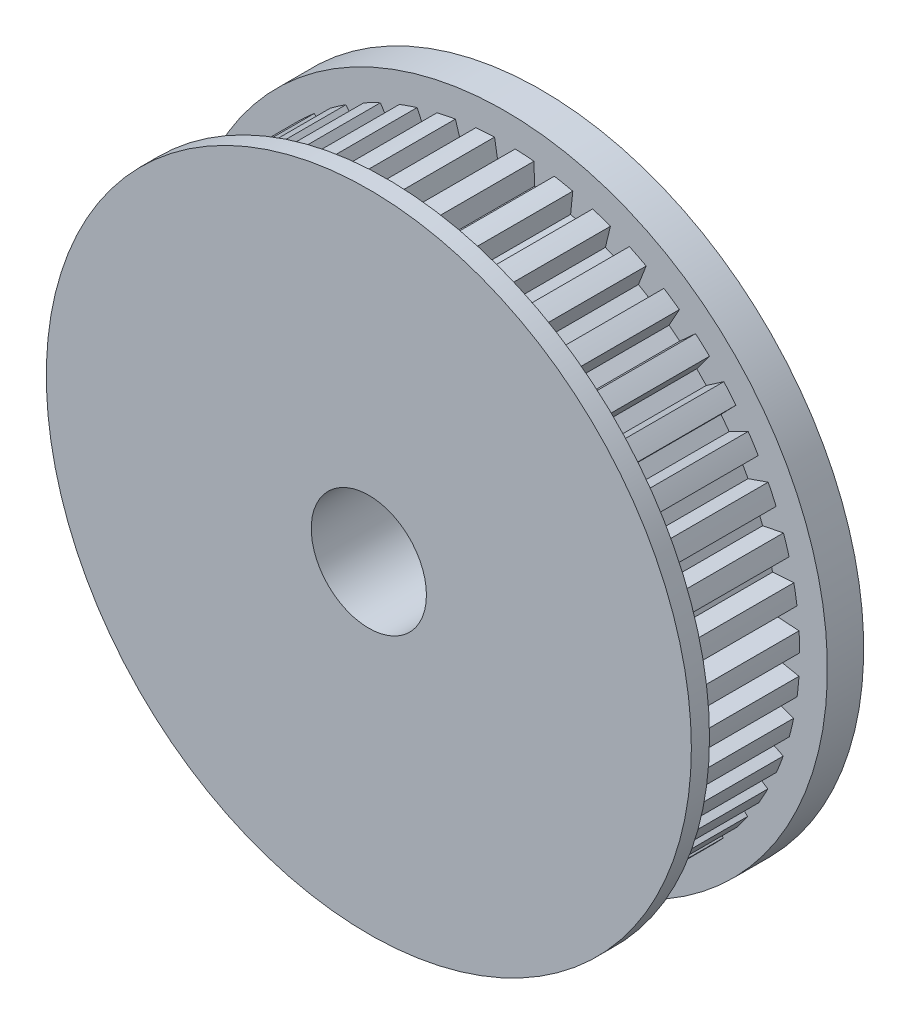
SolidWorks part; units mm, degrees
ref_plane "Front Plane" through (0, 0, 0) normal (0, 0, 1) x (1, 0, 0)
ref_plane "Top Plane" through (0, 0, 0) normal (0, 1, 0) x (1, 0, 0)
ref_plane "Right Plane" through (0, 0, 0) normal (1, 0, 0) x (0, 0, -1)
sketch "Sketch3" plane through (0, 0, 0) normal (0, 0, 1) x (1, 0, 0)
  circle A0 centre (0, 0) radius 16.25
  dimension "D1" = 32.5
extrude "Boss-Extrude2" add sketch "Sketch3" along normal mid plane 6.5
sketch "Sketch1" plane through (0, 0, 0) normal (0, 0, 1) x (1, 0, 0)
  line L0 (-0.375, 15.08) -> (0.375, 15.08)
  line L2 (-0.375, 15.08) -> (-0.6543, 16.7561)
  line L3 (-0.6543, 16.7561) -> (0.6543, 16.7561)
  line L4 (0.6543, 16.7561) -> (0.375, 15.08)
  line L5 (-0.5, 15.83) -> (0.5, 15.83) construction
  point P9 (0, 16.7561)
  point P10 (0, 15.08)
  dimension "D1" = 0.75
  dimension "D2" = 0.75
  dimension "D3" = 1
  dimension "D4" = 15.08
extrude "Cut-Extrude2" cut sketch "Sketch1" against normal through all both and the other way through all
pattern_circular "CirPattern3" count 47 over 360 about axis through (0, 0, 0) along (0, 0, 1) of "Cut-Extrude2"
sketch "Sketch5" plane through (0, 0, -3.25) normal (0, 0, -1) x (-1, 0, 0)
  circle A0 centre (0, 0) radius 17.78
  dimension "D1" = 35.56
extrude "Boss-Extrude3" add sketch "Sketch5" along normal blind 2
sketch "Sketch6" plane through (0, 0, 3.25) normal (0, 0, 1) x (1, 0, 0)
  circle A0 centre (0, 0) radius 17.78
  dimension "D1" = 35.56
extrude "Boss-Extrude4" add sketch "Sketch6" along normal blind 1
sketch "Sketch7" plane through (0, 0, 4.25) normal (0, 0, 1) x (1, 0, 0)
  circle A0 centre (0, 0) radius 3.175
  dimension "D1" = 6.35
extrude "Cut-Extrude3" cut sketch "Sketch7" against normal through all both and the other way through all
